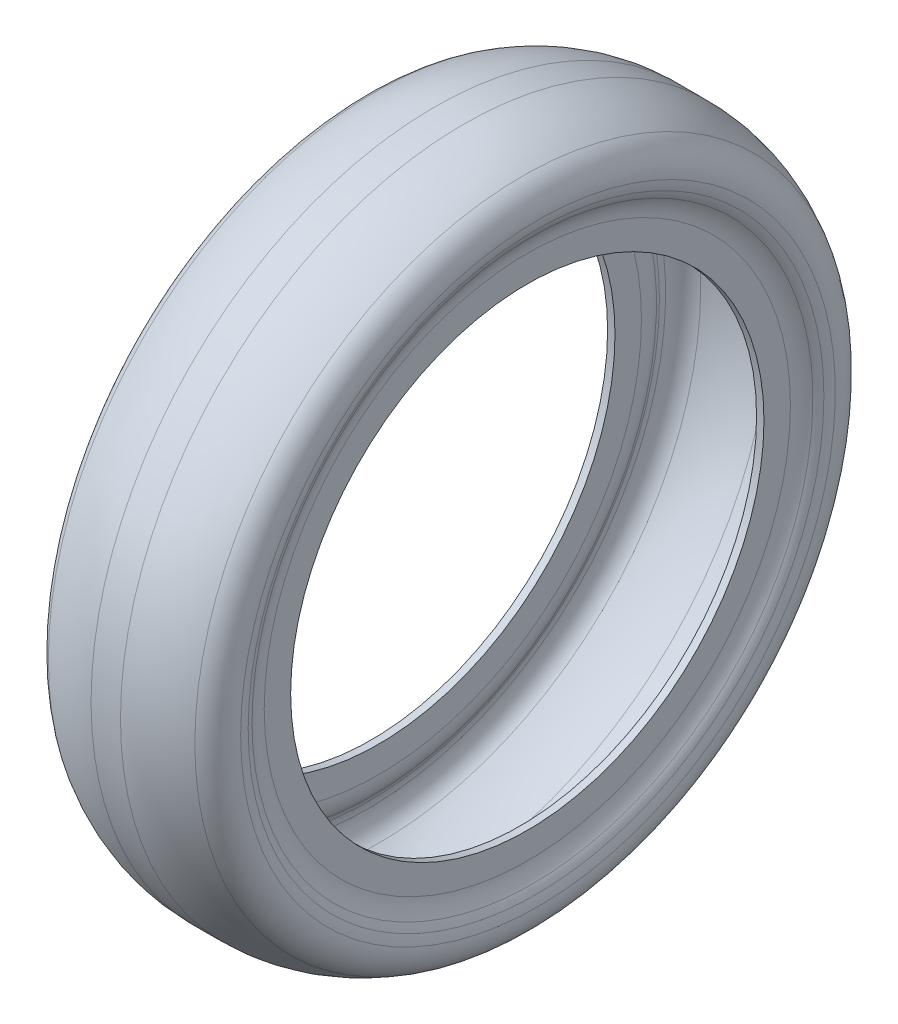
SolidWorks part; units mm, degrees
ref_plane "Plan1" through (0, 0, 0) normal (0, 0, 1) x (1, 0, 0)
ref_plane "Plan2" through (0, 0, 0) normal (0, 1, 0) x (1, 0, 0)
ref_plane "Plan3" through (0, 0, 0) normal (1, 0, 0) x (0, 0, -1)
sketch "Esquisse1" plane through (0, 0, 0) normal (0, 0, 1) x (1, 0, 0)
  line L0 (47.14, 224) -> (47.14, 249.0493)
  line L1 (47.14, -244) -> (47.14, 244) construction
  line L2 (121.14, 220) -> (121.14, 365.4365) construction
  line L3 (189.14, 220) -> (53.14, 220) construction
  line L4 (107.2078, 325) -> (135.0722, 325)
  line L5 (195.14, 224) -> (195.14, 249.0493)
  line L7 (47.14, 244) -> (41.14, 244) construction
  line L9 (130.1362, 0) -> (199.1451, 0) construction
  line L10 (163, 0) -> (111, 0) construction
  line L11 (44.1399, 0) -> (43.6399, 0) construction
  arc A0 (47.14, 249.0493) -> (42.2552, 265.4573) centre (17.14, 249.0493) ccw
  arc A1 (42.2552, 265.4573) -> (38.8824, 272.4616) centre (67.3705, 281.8654) cw
  arc A2 (38.8824, 272.4616) -> (37.0262, 281.4286) centre (76.8665, 285) cw
  arc A3 (190.4866, 310.0223) -> (205.2538, 281.4286) centre (175.3736, 284.1072) cw
  arc A4 (135.0722, 325) -> (190.4866, 310.0223) centre (135.0722, 215) cw
  arc A5 (203.3976, 272.4616) -> (205.2538, 281.4286) centre (165.4135, 285) ccw
  arc A6 (107.2078, 325) -> (51.7934, 310.0223) centre (107.2078, 215) ccw
  arc A7 (51.7934, 310.0223) -> (37.0262, 281.4286) centre (66.9064, 284.1072) ccw
  arc A8 (200.0248, 265.4573) -> (203.3976, 272.4616) centre (174.9095, 281.8654) ccw
  arc A9 (195.14, 249.0493) -> (200.0248, 265.4573) centre (225.14, 249.0493) cw
  point P26 (121.14, 325)
  point P40 (121.14, 325)
  dimension "D1" = 325
  dimension "D2" = 20
  dimension "D3" = 13.9322
  dimension "D4" = 30
  dimension "D5" = 40
  dimension "D6" = 30
  dimension "D8" = 30
  dimension "D9" = 110
  dimension "D7" = 25.0493
  dimension "D10" = 168.2275
revolve "Base-Révol.-Mince" add sketch "Esquisse1" angle 360 about L9
